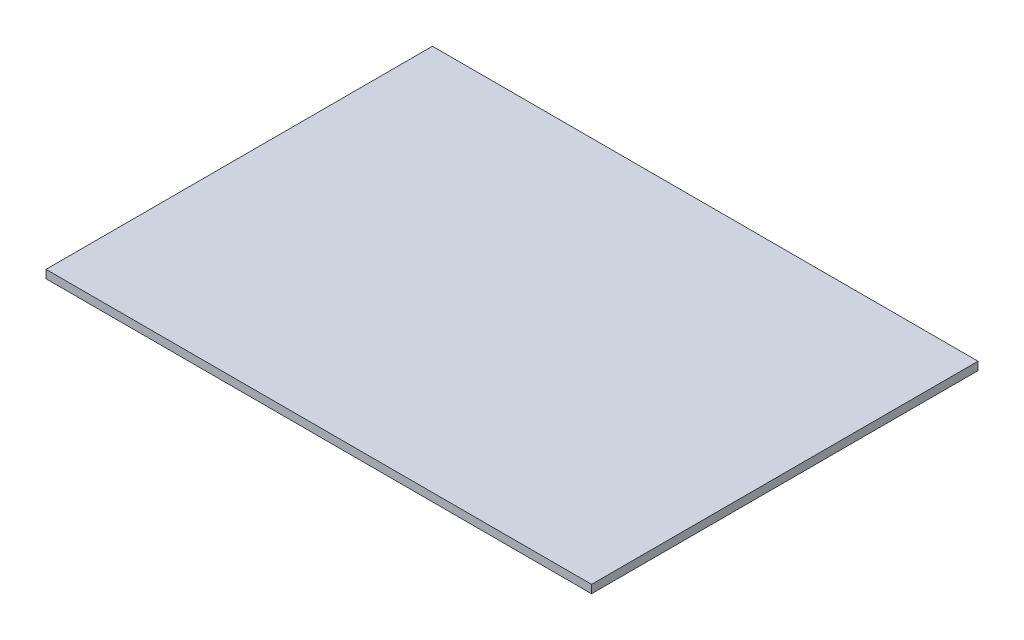
SolidWorks part; units mm, degrees
ref_plane "Front Plane" through (0, 0, 0) normal (0, 0, 1) x (1, 0, 0)
ref_plane "Top Plane" through (0, 0, 0) normal (0, 1, 0) x (1, 0, 0)
ref_plane "Right Plane" through (0, 0, 0) normal (1, 0, 0) x (0, 0, -1)
sketch "Sketch1" plane through (0, 0, 0) normal (0, 1, 0) x (1, 0, 0)
  line L1 (0, 0) -> (1219.2, 0)
  line L2 (0, 0) -> (0, 863.6)
  line L3 (0, 863.6) -> (1219.2, 863.6)
  line L4 (1219.2, 0) -> (1219.2, 863.6)
  dimension "D1" = 863.6
  dimension "D2" = 1219.2
extrude "Boss-Extrude1" add sketch "Sketch1" along normal blind 18.2562 contours L2 L3 L4 L1
